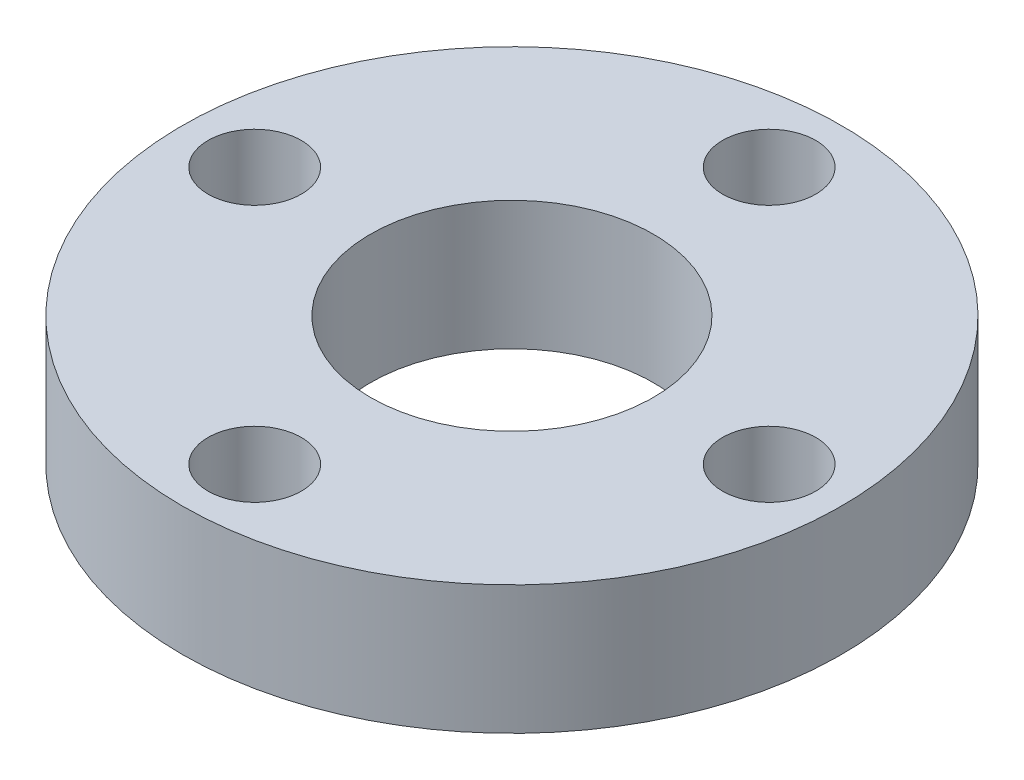
SolidWorks part; units mm, degrees
ref_plane "Front Plane" through (0, 0, 0) normal (0, 0, 1) x (1, 0, 0)
ref_plane "Top Plane" through (0, 0, 0) normal (0, 1, 0) x (1, 0, 0)
ref_plane "Right Plane" through (0, 0, 0) normal (1, 0, 0) x (0, 0, -1)
sketch "Sketch1" plane through (0, 0, 0) normal (0, 1, 0) x (1, 0, 0)
  circle A0 centre (0, 0) radius 10.25
  circle A1 centre (0, 0) radius 4.4
  circle A2 centre (0, 0) radius 8
  circle A3 centre (0, 8) radius 1.45
  circle A4 centre (8, 0) radius 1.45
  circle A5 centre (0, -8) radius 1.45
  circle A6 centre (-8, 0) radius 1.45
  point P16 (0, 0)
  dimension "D1" = 20.5
  dimension "D2" = 8.8
  dimension "D3" = 2.9
  dimension "D4" = 4
extrude "Boss-Extrude1" add sketch "Sketch1" along normal blind 4 contours A0 A6 A2 A3 A4 A5 | A6 A2 A5 A4 A3 A1
